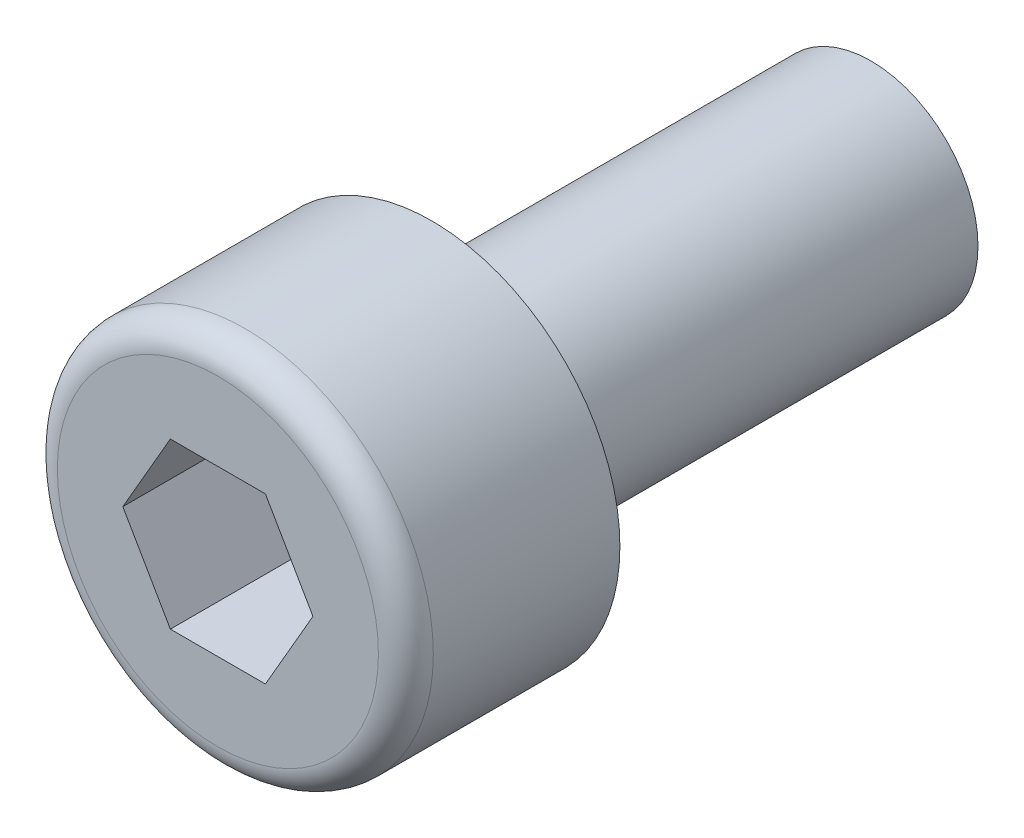
SolidWorks part; units mm, degrees
material "1023 Carbon Steel Sheet (SS)"
ref_plane "Front Plane" through (0, 0, 0) normal (0, 0, 1) x (1, 0, 0)
ref_plane "Top Plane" through (0, 0, 0) normal (0, 1, 0) x (1, 0, 0)
ref_plane "Right Plane" through (0, 0, 0) normal (1, 0, 0) x (0, 0, -1)
sketch "Sketch1" plane through (0, 0, 0) normal (0, 0, 1) x (1, 0, 0)
  circle A0 centre (0, 0) radius 3.425
  dimension "D1" = 6.85
extrude "Boss-Extrude1" add sketch "Sketch1" along normal blind 3.9
sketch "Sketch2" plane through (0, 0, 0) normal (0, 0, -1) x (-1, 0, 0)
  circle A0 centre (0, 0) radius 1.95
  dimension "D1" = 3.9
extrude "Boss-Extrude2" add sketch "Sketch2" along normal blind 8
sketch "Sketch3" plane through (0, 0, 3.9) normal (0, 0, 1) x (1, 0, 0)
  line L1 (1.7321, 0) -> (0.866, 1.5)
  line L2 (0.866, 1.5) -> (-0.866, 1.5)
  line L3 (-0.866, 1.5) -> (-1.7321, 0)
  line L4 (-1.7321, 0) -> (-0.866, -1.5)
  line L5 (-0.866, -1.5) -> (0.866, -1.5)
  line L6 (0.866, -1.5) -> (1.7321, 0)
  circle A0 centre (0, 0) radius 1.5 construction
  dimension "D1" = 3
extrude "Cut-Extrude1" cut sketch "Sketch3" against normal blind 2.5
fillet "Fillet1" radius 0.5 1 edges at (3.425, 0, 3.9)
